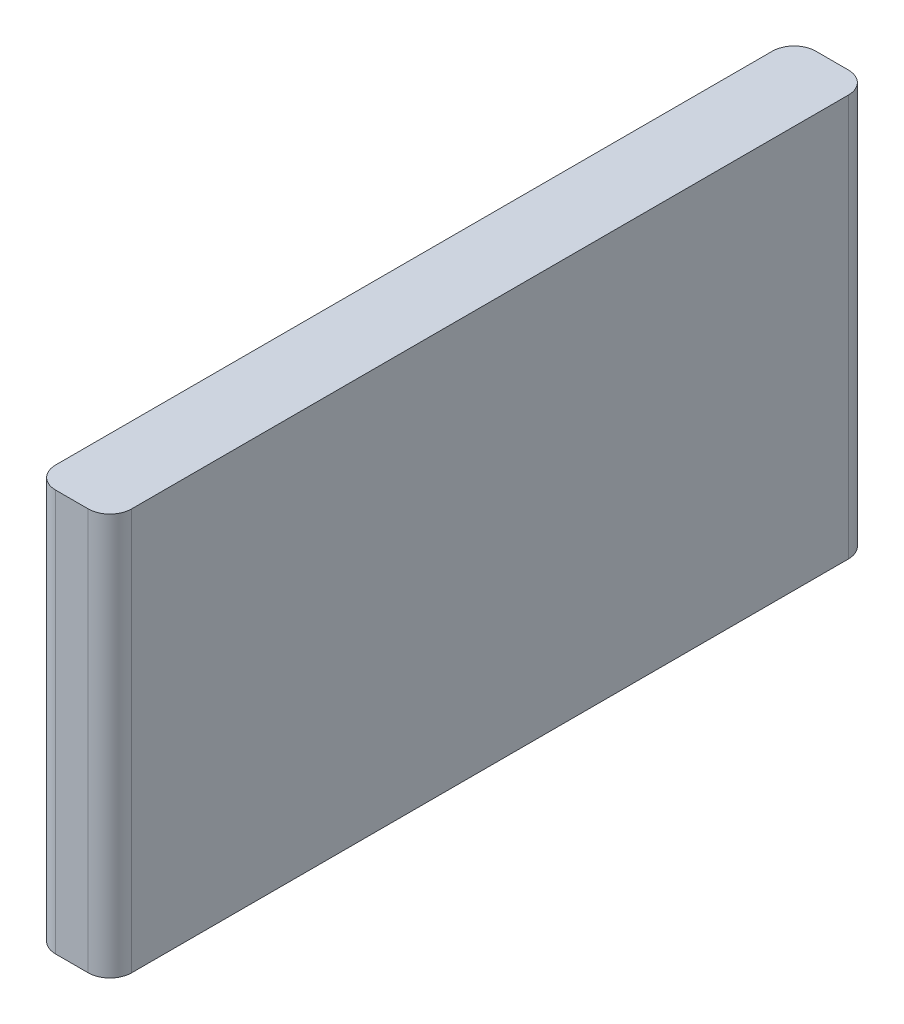
SolidWorks part; units mm, degrees
material "C (Graphite)"
ref_plane "Front" through (0, 0, 0) normal (0, 0, 1) x (1, 0, 0)
ref_plane "Top" through (0, 0, 0) normal (0, 1, 0) x (1, 0, 0)
ref_plane "Right" through (0, 0, 0) normal (1, 0, 0) x (0, 0, -1)
sketch "Sketch1" plane through (0, 0, 0) normal (1, 0, 0) x (0, 0, -1)
  line L1 (0, 0) -> (70, 0)
  line L2 (0, 0) -> (0, 37)
  line L3 (0, 37) -> (70, 37)
  line L4 (70, 0) -> (70, 37)
  dimension "D1" = 70
  dimension "D2" = 37
extrude "Boss-Extrude1" add sketch "Sketch1" along normal blind 7
fillet "Fillet1" radius 2 4 edges at (0, 18.5, 0) (7, 18.5, 0) (7, 18.5, -70) (0, 18.5, -70)
